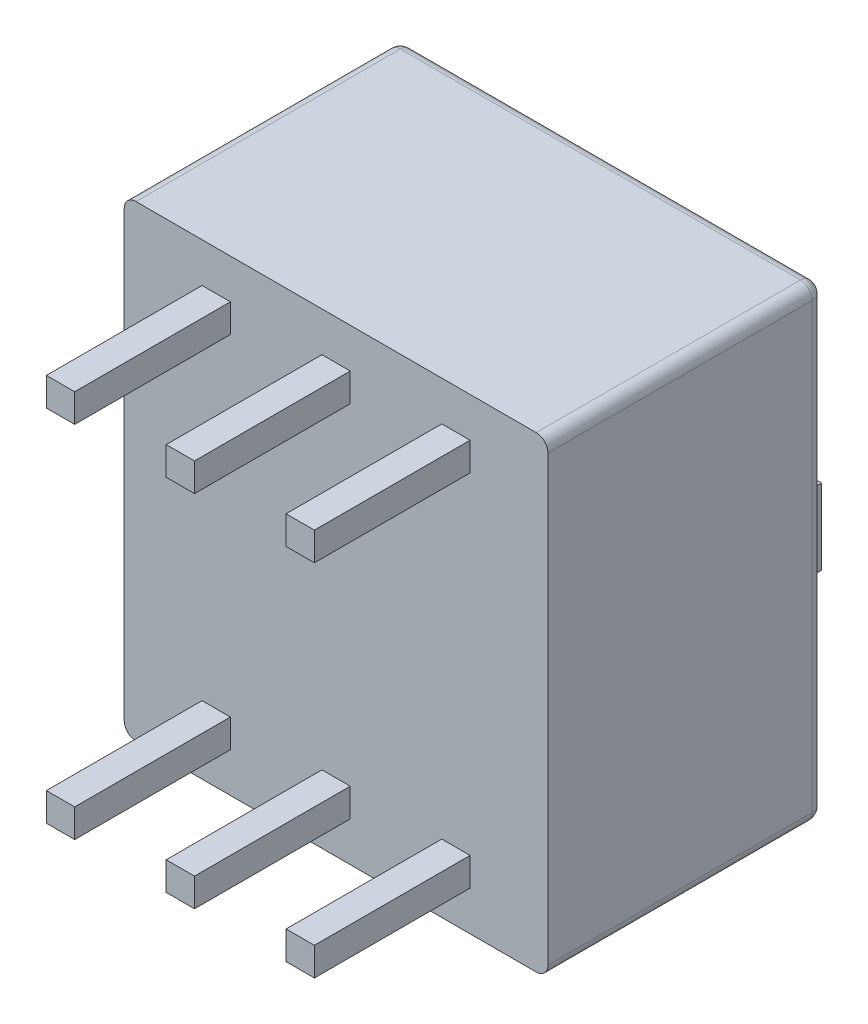
SolidWorks part; units mm, degrees
ref_plane "Ön Düzlem" through (0, 0, 0) normal (0, 0, 1) x (1, 0, 0)
ref_plane "Üst Düzlem" through (0, 0, 0) normal (0, 1, 0) x (1, 0, 0)
ref_plane "Sağ Düzlem" through (0, 0, 0) normal (1, 0, 0) x (0, 0, -1)
sketch "Çizim1" plane through (0, 0, 0) normal (0, 0, 1) x (1, 0, 0)
  line L1 (-4.49, 4.95) -> (4.49, 4.95)
  line L2 (-4.49, 4.95) -> (-4.49, -4.95)
  line L3 (-4.49, -4.95) -> (4.49, -4.95)
  line L4 (4.49, 4.95) -> (4.49, -4.95)
  line L5 (-4.49, 4.95) -> (4.49, -4.95) construction
  line L6 (-4.49, -4.95) -> (4.49, 4.95) construction
  point P0 (0, 0)
extrude "Yükseklik-Ekstrüzyon1" add sketch "Çizim1" along normal blind 5.85
sketch "Çizim2" plane through (0, 0, 0) normal (0, 0, -1) x (-1, 0, 0)
  line L5 (-3.24, -1.6) -> (-1.84, -1.6)
  line L6 (-3.24, -1.6) -> (-3.24, 1.6)
  line L7 (-3.24, 1.6) -> (-1.84, 1.6)
  line L8 (-1.84, -1.6) -> (-1.84, 1.6)
  line L9 (-3.24, -1.6) -> (-1.84, 1.6) construction
  line L10 (-3.24, 1.6) -> (-1.84, -1.6) construction
  line L11 (-0.7, -1.6) -> (0.7, -1.6)
  line L12 (-0.7, -1.6) -> (-0.7, 1.6)
  line L13 (-0.7, 1.6) -> (0.7, 1.6)
  line L14 (0.7, -1.6) -> (0.7, 1.6)
  line L15 (-0.7, -1.6) -> (0.7, 1.6) construction
  line L16 (-0.7, 1.6) -> (0.7, -1.6) construction
  line L17 (1.84, -1.6) -> (3.24, -1.6)
  line L18 (1.84, -1.6) -> (1.84, 1.6)
  line L19 (1.84, 1.6) -> (3.24, 1.6)
  line L20 (3.24, -1.6) -> (3.24, 1.6)
  line L21 (1.84, -1.6) -> (3.24, 1.6) construction
  line L22 (1.84, 1.6) -> (3.24, -1.6) construction
  point P13 (0, 0)
  point P22 (0, 0)
  point P23 (0, 0)
extrude "Kes-Ekstrüzyon1" cut sketch "Çizim2" against normal blind 1
sketch "Çizim3" plane through (0, 0, 1) normal (0, 0, -1) x (-1, 0, 0)
  line L0 (-1.84, -1.6) -> (-1.84, 1.6) construction
  line L1 (-3.24, -1.6) -> (-1.84, -1.6)
  line L2 (-3.24, -1.6) -> (-3.24, 0)
  line L3 (-3.24, 0) -> (-1.84, 0)
  line L4 (-1.84, -1.6) -> (-1.84, 0)
  line L5 (0.7, -1.6) -> (0.7, 1.6) construction
  line L6 (-0.7, -1.6) -> (0.7, -1.6)
  line L7 (-0.7, -1.6) -> (-0.7, 0)
  line L8 (-0.7, 0) -> (0.7, 0)
  line L9 (0.7, -1.6) -> (0.7, 0)
  line L10 (3.24, -1.6) -> (3.24, 1.6) construction
  line L11 (1.84, -1.6) -> (3.24, -1.6)
  line L12 (1.84, -1.6) -> (1.84, 0)
  line L13 (1.84, 0) -> (3.24, 0)
  line L14 (3.24, -1.6) -> (3.24, 0)
extrude "Yükseklik-Ekstrüzyon2" add sketch "Çizim3" along normal blind 2.2
sketch "Çizim4" plane through (0, 0, 1) normal (0, 0, -1) x (-1, 0, 0)
  line L1 (-3.24, 0) -> (-1.84, 0)
  line L2 (-3.24, 0) -> (-3.24, 1.6)
  line L3 (-3.24, 1.6) -> (-1.84, 1.6)
  line L4 (-1.84, 0) -> (-1.84, 1.6)
  line L5 (-0.7, 0) -> (0.7, 0)
  line L6 (-0.7, 0) -> (-0.7, 1.6)
  line L7 (-0.7, 1.6) -> (0.7, 1.6)
  line L8 (0.7, 0) -> (0.7, 1.6)
  line L9 (1.84, 0) -> (3.24, 0)
  line L10 (1.84, 0) -> (1.84, 1.6)
  line L11 (1.84, 1.6) -> (3.24, 1.6)
  line L12 (3.24, 0) -> (3.24, 1.6)
extrude "Yükseklik-Ekstrüzyon3" add sketch "Çizim4" along normal blind 0.9 separate body
fillet "Radyus1" radius 0.25 8 edges at (4.49, 4.95, 2.925) (4.49, -4.95, 2.925) (-4.49, -4.95, 2.925) (-4.49, 4.95, 2.925) (0, -4.95, 0) (4.49, 0, 0) (0, 4.95, 0) (-4.49, 0, 0)
sketch "Çizim5" plane through (0, 0, 5.85) normal (0, 0, 1) x (1, 0, 0)
  line L8 (-2.84, -4.11) -> (-2.24, -4.11)
  line L9 (-2.84, -4.11) -> (-2.84, -3.51)
  line L10 (-2.84, -3.51) -> (-2.24, -3.51)
  line L11 (-2.24, -4.11) -> (-2.24, -3.51)
  line L12 (-2.84, -4.11) -> (-2.24, -3.51) construction
  line L13 (-2.84, -3.51) -> (-2.24, -4.11) construction
  line L14 (-2.84, 3.51) -> (-2.24, 3.51)
  line L15 (-2.84, 3.51) -> (-2.84, 4.11)
  line L16 (-2.84, 4.11) -> (-2.24, 4.11)
  line L17 (-2.24, 3.51) -> (-2.24, 4.11)
  line L18 (-2.84, 3.51) -> (-2.24, 4.11) construction
  line L19 (-2.84, 4.11) -> (-2.24, 3.51) construction
  line L20 (-0.3, -4.11) -> (0.3, -4.11)
  line L21 (-0.3, -4.11) -> (-0.3, -3.51)
  line L22 (-0.3, -3.51) -> (0.3, -3.51)
  line L23 (0.3, -4.11) -> (0.3, -3.51)
  line L24 (-0.3, -4.11) -> (0.3, -3.51) construction
  line L25 (-0.3, -3.51) -> (0.3, -4.11) construction
  line L26 (-0.3, 4.11) -> (0.3, 4.11)
  line L27 (-0.3, 4.11) -> (-0.3, 3.51)
  line L28 (-0.3, 3.51) -> (0.3, 3.51)
  line L29 (0.3, 4.11) -> (0.3, 3.51)
  line L30 (-0.3, 4.11) -> (0.3, 3.51) construction
  line L31 (-0.3, 3.51) -> (0.3, 4.11) construction
  line L32 (2.24, 3.51) -> (2.84, 3.51)
  line L33 (2.24, 3.51) -> (2.24, 4.11)
  line L34 (2.24, 4.11) -> (2.84, 4.11)
  line L35 (2.84, 3.51) -> (2.84, 4.11)
  line L36 (2.24, 3.51) -> (2.84, 4.11) construction
  line L37 (2.24, 4.11) -> (2.84, 3.51) construction
  line L38 (2.24, -4.11) -> (2.84, -4.11)
  line L39 (2.24, -4.11) -> (2.24, -3.51)
  line L40 (2.24, -3.51) -> (2.84, -3.51)
  line L41 (2.84, -4.11) -> (2.84, -3.51)
  line L42 (2.24, -4.11) -> (2.84, -3.51) construction
  line L43 (2.24, -3.51) -> (2.84, -4.11) construction
  point P0 (0, 0)
  point P42 (0, 0)
  point P43 (0, 0)
  point P44 (0, 0)
extrude "Yükseklik-Ekstrüzyon4" add sketch "Çizim5" along normal blind 3.3
